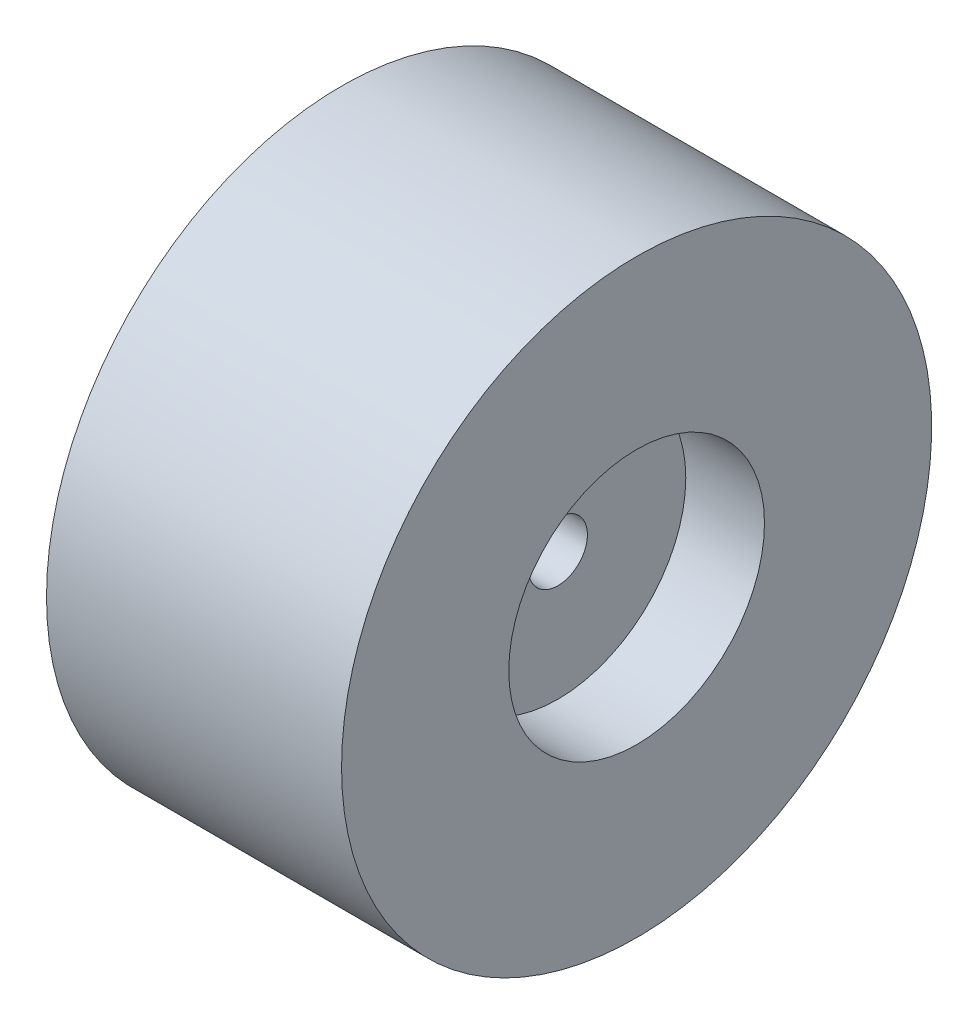
SolidWorks part; units mm, degrees
material "ABS"
ref_plane "Спереди" through (0, 0, 0) normal (0, 0, 1) x (1, 0, 0)
ref_plane "Сверху" through (0, 0, 0) normal (0, 1, 0) x (1, 0, 0)
ref_plane "Справа" through (0, 0, 0) normal (1, 0, 0) x (0, 0, -1)
sketch "Эскиз4" plane through (0, 0, 0) normal (0, 0, 1) x (1, 0, 0)
  line L0 (-30, 0) -> (0, 0) construction
  line L1 (-30, 30) -> (-30, 25.0829)
  line L2 (-30, 25.0829) -> (-28, 23.0829)
  line L3 (-28, 23.0829) -> (-14, 15)
  line L4 (-14, 15) -> (-14, 3)
  line L5 (-14, 3) -> (-8, 3)
  line L6 (-8, 3) -> (-8, 13)
  line L7 (-8, 13) -> (0, 13)
  line L8 (0, 13) -> (0, 30)
  line L9 (0, 30) -> (-30, 30)
  dimension "D1" = 30
  dimension "D2" = 45
  dimension "D3" = 6
  dimension "D4" = 26
  dimension "D5" = 60
  dimension "D6" = 8
  dimension "D7" = 30
  dimension "D8" = 2
  dimension "D9" = 30
  dimension "D10" = 16
revolve "Повернуть1" add sketch "Эскиз4" angle 360 about L0
